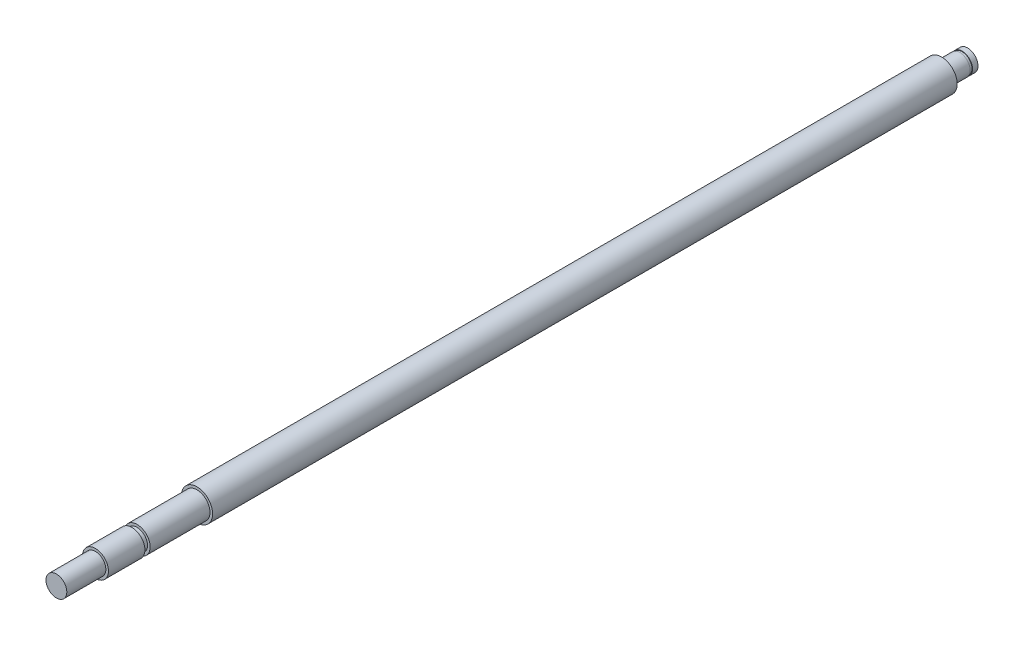
SolidWorks part; units mm, degrees
material "Plain Carbon Steel"
ref_plane "Front Plane" through (0, 0, 0) normal (0, 0, 1) x (1, 0, 0)
ref_plane "Top Plane" through (0, 0, 0) normal (0, 1, 0) x (1, 0, 0)
ref_plane "Right Plane" through (0, 0, 0) normal (1, 0, 0) x (0, 0, -1)
sketch "Sketch1" plane through (0, 0, 0) normal (1, 0, 0) x (0, 0, -1)
  line L0 (-197, 0) -> (153, 0)
  line L1 (153, 0) -> (153, 4)
  line L2 (153, 4) -> (150.9, 4)
  line L3 (150.9, 4) -> (150.9, 3.8)
  line L4 (150.9, 3.8) -> (150, 3.8)
  line L5 (150, 3.8) -> (150, 4)
  line L6 (150, 4) -> (143, 4)
  line L7 (143, 4) -> (143, 6)
  line L8 (143, 6) -> (-143, 6)
  line L9 (-143, 6) -> (-143, 5)
  line L10 (-143, 5) -> (-166, 5)
  line L11 (-166, 5) -> (-166, 4)
  line L12 (-166, 4) -> (-168, 4)
  line L13 (-168, 4) -> (-168, 5)
  line L14 (-168, 5) -> (-182, 5)
  line L15 (-182, 5) -> (-182, 4)
  line L16 (-182, 4) -> (-197, 4)
  line L17 (-197, 4) -> (-197, 0)
  line L18 (0, 55) -> (0, -55) construction
  point P18 (0, 6)
  point P19 (-14.4592, 21.669)
  point P21 (-164.5864, 5)
  point P22 (0, 0)
  dimension "D1" = 2
  dimension "D2" = 15
  dimension "D3" = 16
  dimension "D4" = 39
  dimension "D5" = 0.9
  dimension "D6" = 0.2
  dimension "D7" = 7
  dimension "D8" = 10
  dimension "D9" = 350
  dimension "D10" = 4
  dimension "D11" = 5
  dimension "D12" = 6
revolve "Revolve1" add sketch "Sketch1" angle 360 about L0
